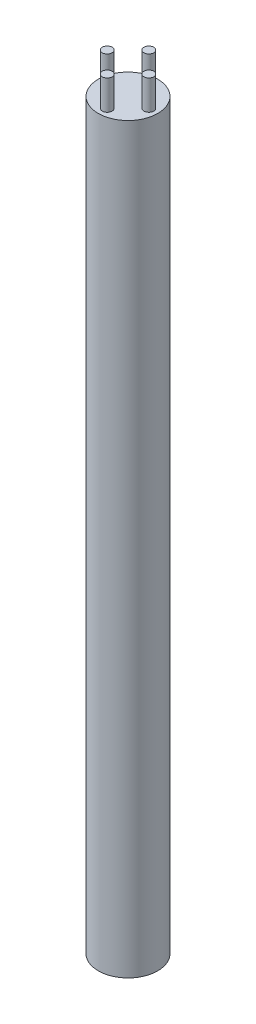
SolidWorks part; units mm, degrees
ref_plane "前视基准面" through (0, 0, 0) normal (0, 0, 1) x (1, 0, 0)
ref_plane "上视基准面" through (0, 0, 0) normal (0, 1, 0) x (1, 0, 0)
ref_plane "右视基准面" through (0, 0, 0) normal (1, 0, 0) x (0, 0, -1)
sketch "草图1" plane through (0, 0, 0) normal (0, 0, 1) x (1, 0, 0)
  line L0 (0, 0) -> (0, 300)
  line L1 (0, 300) -> (10, 300)
  line L2 (10, 300) -> (10, 0)
  line L3 (10, 0) -> (0, 0)
  dimension "D1" = 300
  dimension "D2" = 10
revolve "旋转1" add sketch "草图1" angle 360 about L0
sketch "草图2" plane through (0, 300, 0) normal (0, 1, 0) x (1, 0, 0)
  line L1 (10, 0) -> (0, 0) construction
  circle A0 centre (7, 0) radius 1.65
  circle A1 centre (0, -7) radius 1.65
  circle A2 centre (-7, 0) radius 1.65
  circle A3 centre (0, 7) radius 1.65
  point P14 (0, 0)
  dimension "D1" = 4
extrude "凸台-拉伸1" add sketch "草图2" along normal blind 10
sketch "草图3" plane through (0, 0, 0) normal (0, -1, 0) x (1, 0, 0)
  circle A0 centre (0, 0) radius 10
extrude "切除-拉伸1" cut sketch "草图3" against normal blind 50
